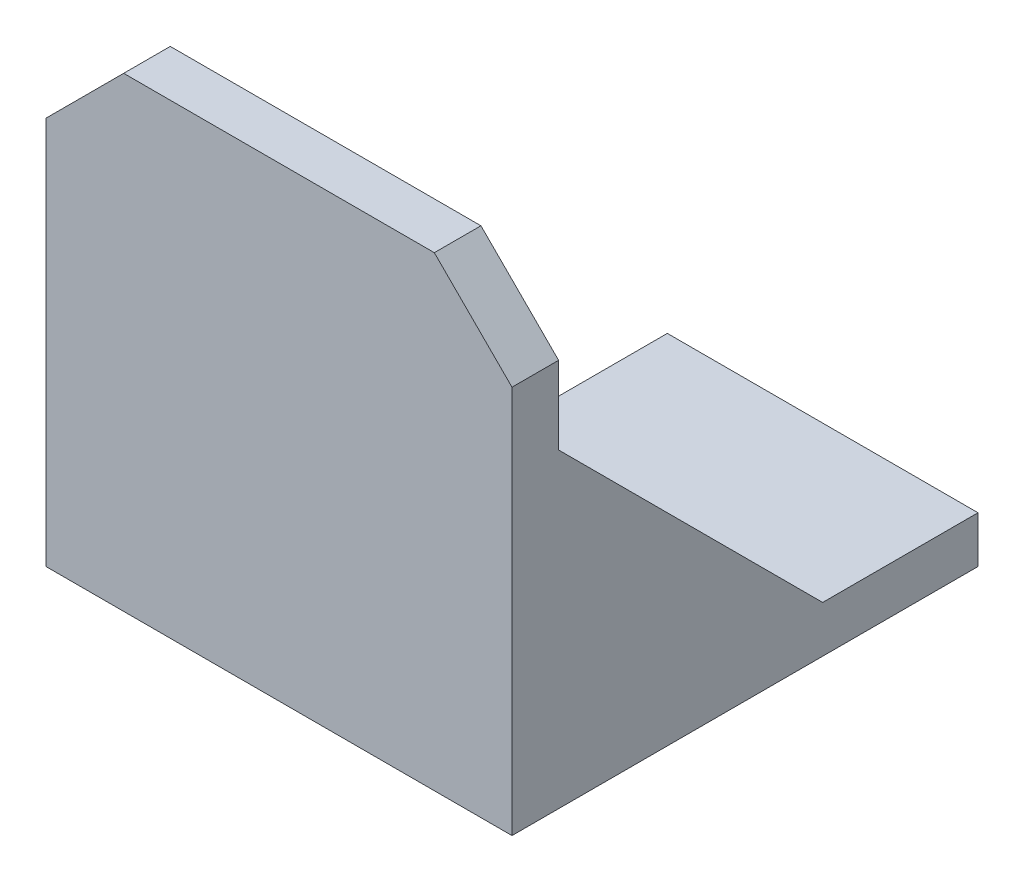
SolidWorks part; units mm, degrees
ref_plane "Front Plane" through (0, 0, 0) normal (0, 0, 1) x (1, 0, 0)
ref_plane "Top Plane" through (0, 0, 0) normal (0, 1, 0) x (1, 0, 0)
ref_plane "Right Plane" through (0, 0, 0) normal (1, 0, 0) x (0, 0, -1)
sketch "Sketch1" plane through (0, 0, 0) normal (0, 1, 0) x (1, 0, 0)
  line L1 (-5, 15) -> (15, 15)
  line L2 (-15, 5) -> (-15, -15)
  line L3 (-15, -15) -> (15, -15)
  line L4 (15, 15) -> (15, -15)
  line L5 (-5, 5) -> (15, -15) construction
  line L6 (-15, -15) -> (15, 15) construction
  line L9 (-15, 5) -> (-5, 5)
  line L10 (-5, 15) -> (-5, 5)
  point P0 (0, 0)
  dimension "D2" = 30
  dimension "D3" = 10
  dimension "D4" = 10
extrude "Boss-Extrude1" add sketch "Sketch1" along normal blind 3
sketch "Sketch2" plane through (0, 3, 0) normal (0, 1, 0) x (1, 0, 0)
  line L0 (15, -15) -> (15, 15) construction
  line L1 (-15, -15) -> (15, -15)
  line L2 (-15, -15) -> (-15, -12)
  line L3 (-15, -12) -> (15, -12)
  line L4 (15, -15) -> (15, -12)
  dimension "D1" = 3
extrude "Boss-Extrude2" add sketch "Sketch2" along normal blind 27
sketch "Sketch3" plane through (-15, 0, 0) normal (-1, 0, 0) x (0, 0, 1)
  line L0 (-5, 3) -> (12, 20)
  line L1 (12, 30) -> (12, 3) construction
  line L2 (12, 20) -> (12, 3)
  line L3 (12, 3) -> (-5, 3)
extrude "Boss-Extrude3" add sketch "Sketch3" against normal blind 2
sketch "Sketch4" plane through (15, 0, 0) normal (1, 0, 0) x (0, 0, -1)
  line L0 (-12, 20) -> (5, 3)
  line L1 (5, 3) -> (-12, 3)
  line L2 (-12, 3) -> (-12, 20)
extrude "Boss-Extrude4" add sketch "Sketch4" against normal blind 2
chamfer "Chamfer1" distance 5 angle 45 2 edges at (15, 30, 13.5) (-15, 30, 13.5)
fillet "Fillet1" radius 3 1 edges at (0, 3, 12)
